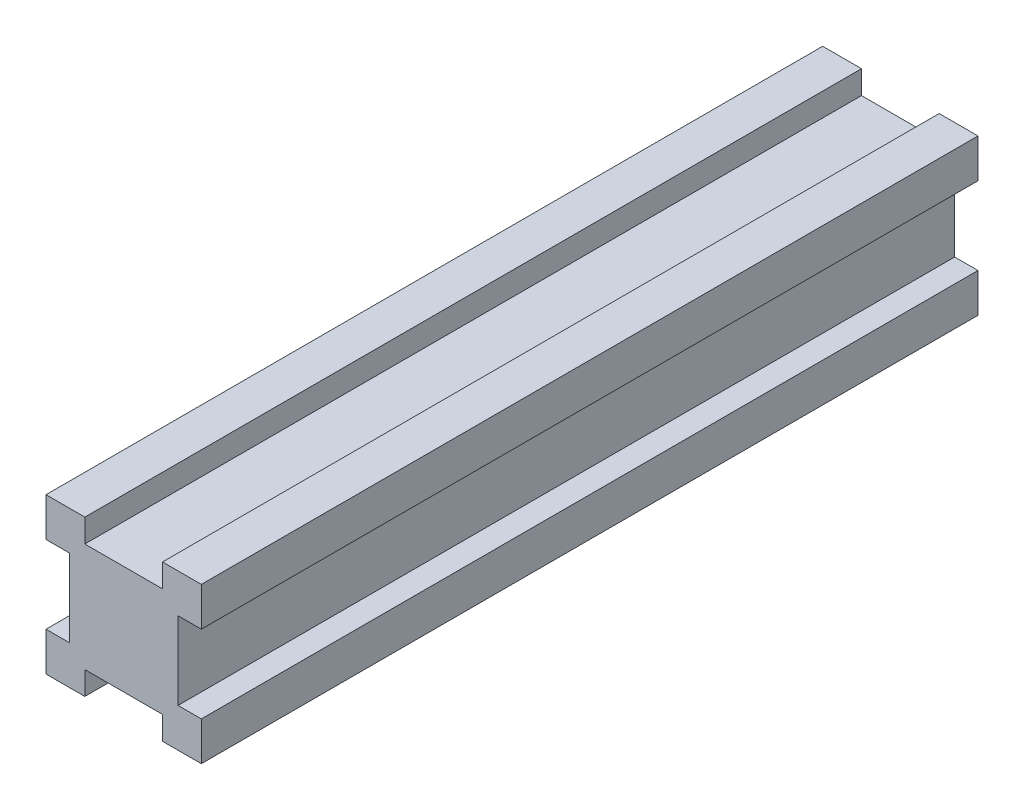
SolidWorks part; units mm, degrees
ref_plane "前视基准面" through (0, 0, 0) normal (0, 0, 1) x (1, 0, 0)
ref_plane "上视基准面" through (0, 0, 0) normal (0, 1, 0) x (1, 0, 0)
ref_plane "右视基准面" through (0, 0, 0) normal (1, 0, 0) x (0, 0, -1)
sketch "草图1" plane through (0, 0, 0) normal (0, 0, 1) x (1, 0, 0)
  line L0 (-5, 10) -> (-5, 7)
  line L1 (-10, -10) -> (10, -10)
  line L2 (-10, -10) -> (-10, -5)
  line L3 (-10, 10) -> (-5, 10)
  line L4 (10, -10) -> (10, -5)
  line L5 (-10, -10) -> (10, 10) construction
  line L6 (-10, 10) -> (10, -10) construction
  line L7 (-5, 7) -> (5, 7)
  line L8 (5, 7) -> (5, 10)
  line L9 (0, 0) -> (0, 17.8745) construction
  line L10 (7, 5) -> (7, -5)
  line L11 (10, 5) -> (7, 5)
  line L12 (7, -5) -> (10, -5)
  line L13 (5, -7) -> (-5, -7)
  line L14 (5, -10) -> (5, -7)
  line L15 (-5, -7) -> (-5, -10)
  line L16 (-7, -5) -> (-7, 5)
  line L17 (-10, -5) -> (-7, -5)
  line L18 (-7, 5) -> (-10, 5)
  line L19 (10, 5) -> (10, 10)
  line L20 (5, 10) -> (10, 10)
  line L21 (-10, 5) -> (-10, 10)
  point P0 (0, 0)
  point P27 (0, 0)
  dimension "D1" = 20
  dimension "D2" = 20
  dimension "D3" = 10
  dimension "D4" = 3
  dimension "D5" = 4
extrude "凸台-拉伸1" add sketch "草图1" along normal mid plane 100 contours L21 L18 L16 L17 L2 L1 L15 L13 L14 L4 L12 L10 L11 L19 L20 L8 L7 L0 L3
